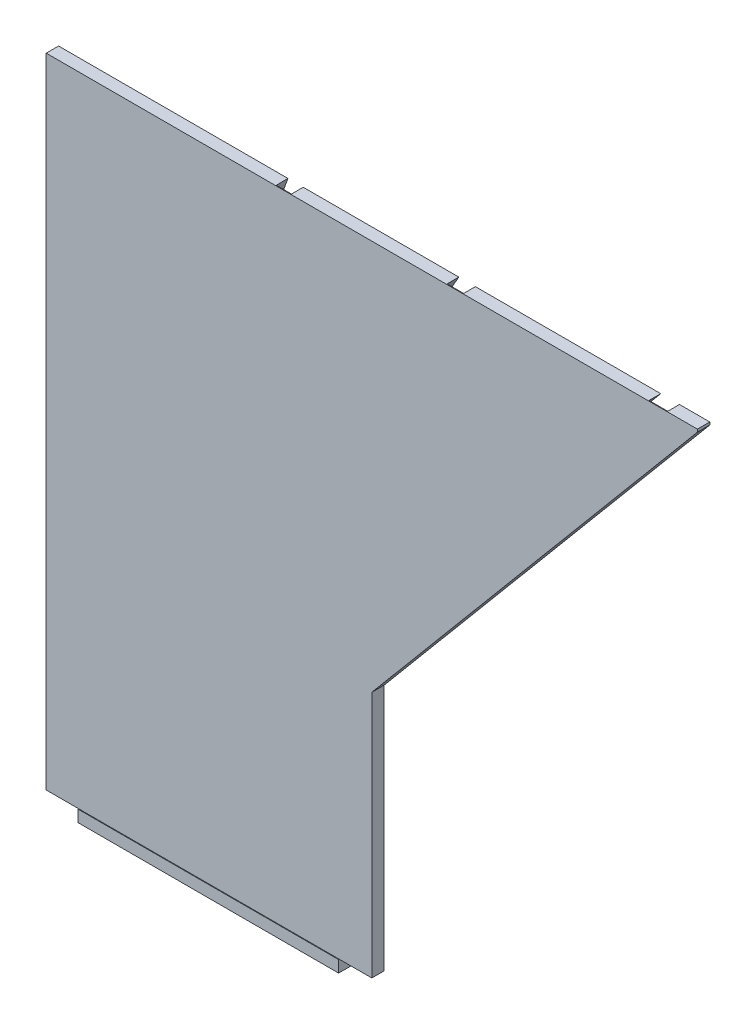
SolidWorks part; units mm, degrees
ref_plane "Front Plane" through (0, 0, 0) normal (0, 0, 1) x (1, 0, 0)
ref_plane "Top Plane" through (0, 0, 0) normal (0, 1, 0) x (1, 0, 0)
ref_plane "Right Plane" through (0, 0, 0) normal (1, 0, 0) x (0, 0, -1)
sketch "Sketch1" plane through (0, 0, 0) normal (0, 0, 1) x (1, 0, 0)
  line L0 (-37.265, -36.6025) -> (12.735, 50)
  line L1 (-50, 50) -> (50, 50)
  line L2 (-50, 50) -> (-50, -50)
  line L3 (-50, -50) -> (50, -50)
  line L4 (50, 50) -> (50, -50)
  line L5 (-50, 50) -> (50, -50) construction
  line L6 (-50, -50) -> (50, 50) construction
  line L7 (-45, -50) -> (-40, -50)
  line L8 (-47.805, -43.9693) -> (-13.603, 50)
  line L9 (-20.3688, -26.6044) -> (43.91, 50)
  line L12 (42.474, 50) -> (-21.2114, -25.8974)
  line L15 (-14.7736, 50) -> (-48.8387, -43.593)
  line L16 (-12.4324, 50) -> (-46.7713, -44.3455)
  line L17 (45.3459, 50) -> (-19.5261, -27.3115)
  line L20 (11.4649, 50) -> (-38.2176, -36.0525)
  line L21 (-50, 50) -> (-150, 50)
  line L22 (-150, 50) -> (-150, -50)
  line L23 (-150, -50) -> (-50, -50)
  line L24 (-50, -50) -> (-50, 50)
  line L25 (-150, 50) -> (-50, 50)
  line L26 (50, 50) -> (50, 150)
  line L27 (-150, 50) -> (-150, 150)
  line L28 (-50, 50) -> (50, 150)
  line L29 (-50, -50) -> (-45, -50)
  line L30 (14.0052, 50) -> (-36.3123, -37.1525)
  line L34 (-13.603, 50) -> (-47.805, -43.9693)
  line L35 (-47.805, -43.9693) -> (-46.7713, -44.3455)
  line L36 (-47.805, -43.9693) -> (-48.8387, -43.593)
  line L37 (12.735, 50) -> (-37.265, -36.6025)
  line L38 (-37.265, -36.6025) -> (-36.3123, -37.1525)
  line L39 (-37.265, -36.6025) -> (-38.2176, -36.0525)
  line L40 (43.91, 50) -> (-20.3688, -26.6044)
  line L41 (-20.3688, -26.6044) -> (-19.5261, -27.3115)
  line L42 (-20.3688, -26.6044) -> (-21.2114, -25.8974)
  line L43 (0, -50) -> (0, -10)
  line L44 (0, -10) -> (50, 49.5877)
  line L45 (0, -50) -> (-5, -50)
  line L48 (-50, -50) -> (-45, -50)
  line L50 (-45, -50) -> (-45, -48)
  line L51 (-45, -48) -> (-5, -48)
  line L52 (-5, -48) -> (-5, -50)
  line L53 (-45, -48) -> (-50, -48)
  line L54 (-5, -48) -> (0, -48)
  point P0 (0, 0)
  dimension "D1" = 100
  dimension "D2" = 100
  dimension "D3" = 60
  dimension "D4" = 50
  dimension "D5" = 70
  dimension "D6" = 1.1
  dimension "D7" = 50
extrude "Boss-Extrude1" add sketch "Sketch1" along normal blind 1.9
ref_plane "Plane1" through (0, 0, 0) normal (0, 0, -1) x (-1, 0, 0)
sketch "Sketch2" plane through (0, 0, 0) normal (0, 0, -1) x (-1, 0, 0)
  line L0 (-45.3459, 50) -> (-42.474, 50)
  line L1 (-42.474, 50) -> (21.2114, -25.8974)
  line L2 (21.2114, -25.8974) -> (19.5261, -27.3115)
  line L3 (19.5261, -27.3115) -> (-45.3459, 50)
  line L4 (-14.0052, 50) -> (36.3123, -37.1525)
  line L5 (36.3123, -37.1525) -> (38.2176, -36.0525)
  line L6 (38.2176, -36.0525) -> (-11.4649, 50)
  line L7 (-11.4649, 50) -> (-14.0052, 50)
  line L8 (12.4324, 50) -> (14.7736, 50)
  line L9 (14.7736, 50) -> (48.8387, -43.593)
  line L10 (48.8387, -43.593) -> (46.7713, -44.3455)
  line L11 (46.7713, -44.3455) -> (12.4324, 50)
ref_plane "Plane2" through (0, 0, 1.9) normal (0, 0, 1) x (1, 0, 0)
sketch "Sketch6" plane through (0, 0, 1.9) normal (0, 0, 1) x (1, 0, 0)
  line L0 (-45, -48) -> (-5, -48)
  line L1 (-5, -48) -> (-5, -50)
  line L2 (-5, -50) -> (-45, -50)
  line L3 (-45, -50) -> (-45, -48)
extrude "Boss-Extrude6" add sketch "Sketch6" along normal blind 0.1
chamfer "Chamfer2" distance 0.2 angle 45 4 edges at (-45, -50, 1) (-25, -50, 2) (-5, -50, 1) (-25, -50, 0)
sketch "Sketch9" plane through (0, 0, 1.9) normal (0, 0, 1) x (1, 0, 0)
  line L0 (-14.7736, 50) -> (-12.4324, 50)
  line L1 (-12.4324, 50) -> (-46.7713, -44.3455)
  line L2 (-46.7713, -44.3455) -> (-48.8387, -43.593)
  line L3 (-48.8387, -43.593) -> (-14.7736, 50)
  line L4 (11.4649, 50) -> (14.0052, 50)
  line L5 (14.0052, 50) -> (-36.3123, -37.1525)
  line L6 (-36.3123, -37.1525) -> (-38.2176, -36.0525)
  line L7 (-38.2176, -36.0525) -> (11.4649, 50)
  line L8 (42.474, 50) -> (45.3459, 50)
  line L9 (45.3459, 50) -> (-19.5261, -27.3115)
  line L10 (-19.5261, -27.3115) -> (-21.2114, -25.8974)
  line L11 (-21.2114, -25.8974) -> (42.474, 50)
extrude "Boss-Extrude7" add sketch "Sketch9" against normal blind 0.1
sketch "Sketch10" plane through (0, 0, 1.9) normal (0, 0, 1) x (1, 0, 0)
  line L0 (-50, 50) -> (-50, -50)
  line L1 (-5.2, -50) -> (-50, -50)
  line L2 (-50, -48) -> (-45, -48)
  line L3 (-45, -48) -> (-45, -50)
